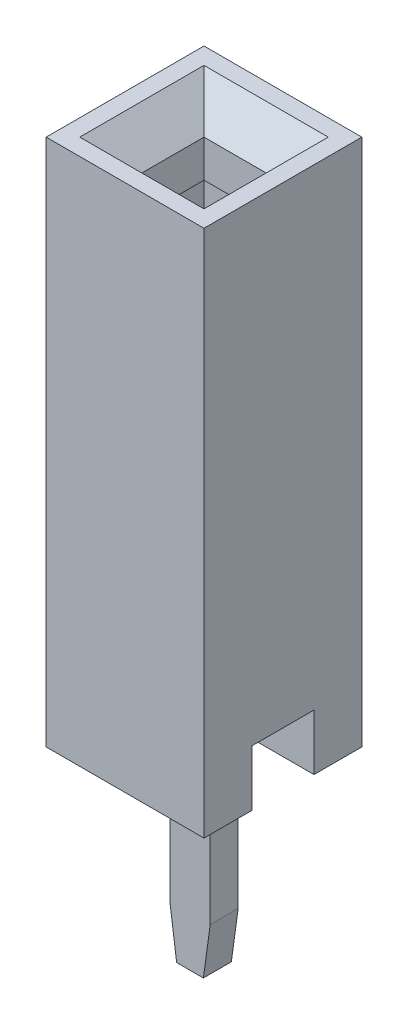
SolidWorks part; units mm, degrees
ref_plane "Vorne" through (0, 0, 0) normal (0, 0, 1) x (1, 0, 0)
ref_plane "Oben" through (0, 0, 0) normal (0, 1, 0) x (1, 0, 0)
ref_plane "Rechts" through (0, 0, 0) normal (1, 0, 0) x (0, 0, -1)
sketch "Sketch1" plane through (0, 0, 0) normal (0, 1, 0) x (1, 0, 0)
  line L1 (1.27, -1.27) -> (-1.27, -1.27)
  line L2 (1.27, -1.27) -> (1.27, 1.27)
  line L3 (1.27, 1.27) -> (-1.27, 1.27)
  line L4 (-1.27, -1.27) -> (-1.27, 1.27)
  line L5 (1.27, -1.27) -> (-1.27, 1.27) construction
  line L6 (1.27, 1.27) -> (-1.27, -1.27) construction
  point P0 (0, 0)
  dimension "D1" = 2.54
extrude "Boss-Extrude1" add sketch "Sketch1" along normal blind 8.5
shell "Shell1" thickness 0.77
chamfer "Chamfer1" distance 0.5 angle 45 4 edges at (-0.5, 8.5, 0) (0, 8.5, 0.5) (0.5, 8.5, 0) (0, 8.5, -0.5)
sketch "Sketch2" plane through (0, 0, 0) normal (1, 0, 0) x (0, 0, -1)
  line L0 (1.27, 0) -> (-1.27, 0) construction
  line L1 (0.5, 0) -> (-0.5, 0)
  line L2 (0.5, 0) -> (0.5, 0.9)
  line L3 (0.5, 0.9) -> (-0.5, 0.9)
  line L4 (-0.5, 0) -> (-0.5, 0.9)
  dimension "D1" = 1
  dimension "D2" = 0.9
extrude "Cut-Extrude1" cut sketch "Sketch2" against normal through all both and the other way through all
sketch "Sketch3" plane through (0, 0, 0) normal (0, 1, 0) x (1, 0, 0)
  line L1 (1, 1) -> (-1, 1)
  line L2 (1, 1) -> (1, -1)
  line L3 (1, -1) -> (-1, -1)
  line L4 (-1, 1) -> (-1, -1)
  line L5 (1, 1) -> (-1, -1) construction
  line L6 (1, -1) -> (-1, 1) construction
  point P0 (0, 0)
  dimension "D1" = 2
extrude "Cut-Extrude3" cut sketch "Sketch3" along normal blind 6 from offset 1.4
sketch "Sketch4" plane through (0, 0, 0) normal (0, 0, 1) x (1, 0, 0)
  line L0 (-1, 7.3) -> (-1, 1.4)
  line L1 (0, 8.5) -> (0, 0) construction
  line L2 (-0.325, -2.2) -> (-0.215, -3)
  line L3 (-0.6, 4.9) -> (-0.6, 2.8)
  line L4 (-0.325, 1.4) -> (-0.325, -2.2)
  line L5 (-0.5, 1.4) -> (0.5, 1.4) construction
  line L6 (-0.325, 1.4) -> (-1, 1.4)
  line L7 (-0.215, -3) -> (0.215, -3)
  line L8 (-1.27, 0) -> (1.27, 0) construction
  line L9 (-0.8375, 7.3296) -> (-0.6, 6.7)
  line L10 (0.8375, 7.3296) -> (0.6, 6.7)
  line L11 (0.325, 1.4) -> (1, 1.4)
  line L12 (0.325, 1.4) -> (0.325, -2.2)
  line L13 (0.6, 4.9) -> (0.6, 2.8)
  line L14 (0.325, -2.2) -> (0.215, -3)
  line L15 (1, 7.3) -> (1, 1.4)
  arc A0 (-0.6, 2.8) -> (0.6, 2.8) centre (0, 2.8) ccw
  arc A1 (-0.6, 4.9) -> (-0.6, 6.7) centre (-2.9859, 5.8) ccw
  arc A2 (-1, 7.3) -> (-0.8375, 7.3296) centre (-0.9161, 7.3) cw
  arc A3 (1, 7.3) -> (0.8375, 7.3296) centre (0.9161, 7.3) ccw
  arc A4 (0.6, 4.9) -> (0.6, 6.7) centre (2.9859, 5.8) cw
  point P29 (0, -3)
  dimension "D10" = 2.55
  dimension "D1" = 1
  dimension "D2" = 0.6
  dimension "D3" = 0.325
  dimension "D4" = 1.4
  dimension "D5" = 0.215
  dimension "D6" = 0.8
  dimension "D7" = 3
  dimension "D8" = 3.5
  dimension "D9" = 1.8
  dimension "D11" = 5.9
extrude "Boss-Extrude2" add sketch "Sketch4" along normal mid plane 0.45
